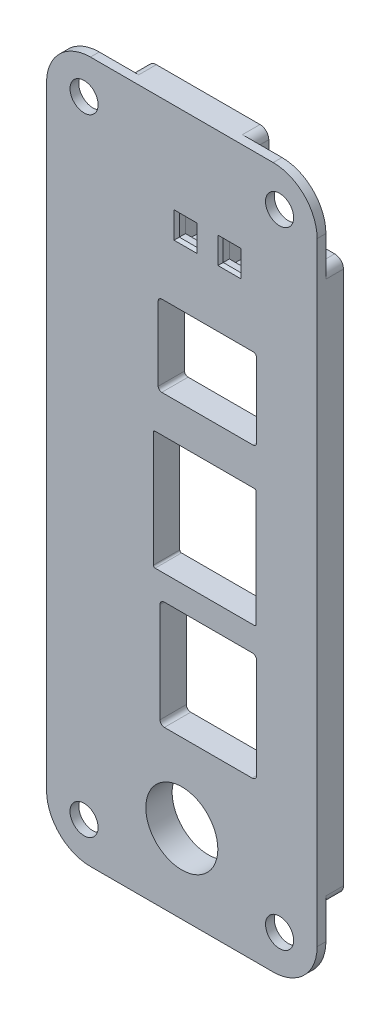
SolidWorks part; units mm, degrees
ref_plane "Front Plane" through (0, 0, 0) normal (0, 0, 1) x (1, 0, 0)
ref_plane "Top Plane" through (0, 0, 0) normal (0, 1, 0) x (1, 0, 0)
ref_plane "Right Plane" through (0, 0, 0) normal (1, 0, 0) x (0, 0, -1)
other "Configuration Table"
sketch "草图1" plane through (0, 0, 0) normal (0, 0, 1) x (1, 0, 0)
  line L0 (47.5, 0) -> (47.4, 0) construction
  line L1 (47.5, -35) -> (47.5, 35) construction
  line L2 (47.4, -34.9) -> (47.4, 34.9)
  line L3 (32, 40) -> (32, 39.9) construction
  line L4 (42.5, 40) -> (21.5, 40) construction
  line L5 (21.6, 39.9) -> (42.4, 39.9)
  line L8 (21.6, -39.9) -> (42.4, -39.9)
  line L9 (21.6, -39.9) -> (42.4, -39.9)
  line L10 (21.6, 39.9) -> (42.4, 39.9)
  line L12 (31.4138, 26.9024) -> (33.4138, 26.9024)
  line L15 (16.5, 0) -> (16.6, 0) construction
  line L16 (40.4138, -15.8026) -> (40.5139, -15.8026) construction
  line L17 (40.5139, -21.4776) -> (40.5139, -10.1276)
  line L18 (16.6, -34.9) -> (16.6, 34.9)
  line L19 (30.0139, -21.9776) -> (40.0139, -21.9776)
  line L20 (37.4138, 28.1024) -> (32.4138, 28.1024) construction
  line L21 (31.4138, 26.9024) -> (31.4138, 29.3024)
  line L22 (30.0139, -9.6276) -> (40.0139, -9.6276)
  line L23 (31.4138, 29.3024) -> (33.4138, 29.3024)
  line L24 (33.4138, 26.9024) -> (33.4138, 29.3024)
  line L25 (29.5139, -21.4776) -> (29.5139, -10.1276)
  line L26 (31.4138, 26.9024) -> (33.4138, 29.3024) construction
  line L27 (31.4138, 29.3024) -> (33.4138, 26.9024) construction
  line L28 (36.4138, 29.3024) -> (38.4138, 29.3024)
  line L29 (36.4138, 29.3024) -> (36.4138, 26.9024)
  line L30 (36.4138, 26.9024) -> (38.4138, 26.9024)
  line L31 (40.3644, -0.0546) -> (40.465, -0.0546) construction
  line L32 (38.4138, 29.3024) -> (38.4138, 26.9024)
  line L33 (36.4138, 29.3024) -> (38.4138, 26.9024) construction
  line L34 (40.465, 6.4954) -> (40.465, -6.6046)
  line L35 (34.6144, 6.5954) -> (34.6144, 6.6954) construction
  line L36 (28.9639, 6.6954) -> (40.265, 6.6954)
  line L37 (36.4138, 26.9024) -> (38.4138, 29.3024) construction
  line L38 (28.8639, -0.0546) -> (28.7639, -0.0546) construction
  line L39 (28.7639, 6.4954) -> (28.7639, -6.6046)
  line L40 (34.6139, -6.7046) -> (34.6139, -6.8046) construction
  line L41 (28.9639, -6.8046) -> (40.265, -6.8046)
  line L50 (40.5138, 11.3024) -> (40.5138, 19.7024)
  line L51 (29.7138, 20.1024) -> (40.1138, 20.1024)
  line L52 (29.3138, 11.3024) -> (29.3138, 19.7024)
  line L53 (29.7138, 10.9024) -> (40.1138, 10.9024)
  arc A0 (42.4, -39.9) -> (47.4, -34.9) centre (42.4, -34.9) ccw
  arc A1 (21.6, -39.9) -> (16.6, -34.9) centre (21.6, -34.9) cw
  arc A2 (47.4, 34.9) -> (42.4, 39.9) centre (42.4, 34.9) ccw
  arc A3 (16.6, 34.9) -> (21.6, 39.9) centre (21.6, 34.9) cw
  arc A4 (30.0139, -21.9776) -> (29.5139, -21.4776) centre (30.0139, -21.4776) cw
  arc A5 (40.0139, -21.9776) -> (40.5139, -21.4776) centre (40.0139, -21.4776) ccw
  arc A6 (40.5139, -10.1276) -> (40.0139, -9.6276) centre (40.0139, -10.1276) ccw
  arc A7 (29.5139, -10.1276) -> (30.0139, -9.6276) centre (30.0139, -10.1276) cw
  arc A8 (28.7639, 6.4954) -> (28.9639, 6.6954) centre (28.9639, 6.4954) cw
  arc A9 (40.465, 6.4954) -> (40.265, 6.6954) centre (40.265, 6.4954) ccw
  arc A10 (28.9639, -6.8046) -> (28.7639, -6.6046) centre (28.9639, -6.6046) cw
  arc A11 (40.265, -6.8046) -> (40.465, -6.6046) centre (40.265, -6.6046) ccw
  arc A12 (29.7138, 10.9024) -> (29.3138, 11.3024) centre (29.7138, 11.3024) cw
  arc A13 (40.1138, 10.9024) -> (40.5138, 11.3024) centre (40.1138, 11.3024) ccw
  arc A14 (40.5138, 19.7024) -> (40.1138, 20.1024) centre (40.1138, 19.7024) ccw
  arc A15 (29.3138, 19.7024) -> (29.7138, 20.1024) centre (29.7138, 19.7024) cw
  point P16 (32, -39.9)
  point P36 (40.5139, -15.8026)
  point P39 (35.0139, -21.9776)
  point P46 (35.0139, -9.6276)
  point P53 (29.5139, -15.8026)
  point P58 (40.4644, -0.0546)
  point P72 (40.465, -0.0546)
  point P78 (34.6144, 6.6954)
  point P84 (28.7639, -0.0546)
  point P89 (34.6139, -6.8046)
  point P112 (40.5138, 15.5024)
  point P117 (34.9138, 20.1024)
  point P118 (29.3138, 15.5024)
  point P123 (34.9138, 10.9024)
  dimension "D1" = 5
  dimension "D2" = 0.5
  dimension "D3" = 0.2
  dimension "D4" = 0.4
  dimension "D5" = 8
extrude "凸台-拉伸1" add sketch "草图1" against normal blind 3
sketch "草图2" plane through (0, 0, -3) normal (0, 0, -1) x (-1, 0, 0)
  line L0 (-16.6, -19) -> (-16.6, 19)
  line L2 (-16.6, -34.9) -> (-16.6, 34.9) construction
  line L3 (-16.6, -19) -> (-27.6, -19)
  line L4 (-27.6, -19) -> (-27.6, 19)
  line L5 (-27.6, 19) -> (-16.6, 19)
  point P5 (-16.6, 0)
extrude "切除-拉伸1" cut sketch "草图2" against normal blind 1
sketch "草图3" plane through (0, 0, -3) normal (0, 0, -1) x (-1, 0, 0)
  line L0 (-47.4, -31.4) -> (-38.9, -31.4)
  line L1 (-47.4, -34.9) -> (-47.4, 34.9) construction
  line L2 (-38.9, -31.4) -> (-38.9, -39.9)
  line L3 (-21.6, -39.9) -> (-42.4, -39.9) construction
  line L5 (-42.4, -39.9) -> (-38.9, -39.9)
  line L6 (-47.4, -34.9) -> (-47.4, -31.4)
  line L7 (-47.4, 0) -> (-16.6, 0) construction
  line L8 (-16.6, -19) -> (-16.6, 19) construction
  line L9 (-32, 0) -> (-32, -4.0641) construction
  line L10 (-47.4, 34.9) -> (-47.4, 31.4)
  line L11 (-42.4, 39.9) -> (-38.9, 39.9)
  line L12 (-38.9, 31.4) -> (-38.9, 39.9)
  line L13 (-47.4, 31.4) -> (-38.9, 31.4)
  line L15 (-16.6, 31.4) -> (-25.1, 31.4)
  line L16 (-25.1, 31.4) -> (-25.1, 39.9)
  line L17 (-21.6, 39.9) -> (-25.1, 39.9)
  line L18 (-16.6, 34.9) -> (-16.6, 31.4)
  line L19 (-16.6, -34.9) -> (-16.6, -31.4)
  line L20 (-21.6, -39.9) -> (-25.1, -39.9)
  line L21 (-25.1, -31.4) -> (-25.1, -39.9)
  line L22 (-16.6, -31.4) -> (-25.1, -31.4)
  arc A0 (-42.4, -39.9) -> (-47.4, -34.9) centre (-42.4, -34.9) cw
  arc A1 (-42.4, 39.9) -> (-47.4, 34.9) centre (-42.4, 34.9) ccw
  arc A2 (-21.6, 39.9) -> (-16.6, 34.9) centre (-21.6, 34.9) cw
  arc A3 (-21.6, -39.9) -> (-16.6, -34.9) centre (-21.6, -34.9) ccw
extrude "切除-拉伸2" cut sketch "草图3" against normal blind 2
sketch "草图4" plane through (0, 0, -1) normal (0, 0, -1) x (-1, 0, 0)
  line L0 (-47.4, 0) -> (-16.6, 0) construction
  line L1 (-47.4, -31.4) -> (-47.4, 31.4) construction
  line L2 (-16.6, -19) -> (-16.6, 19) construction
  line L3 (-32, 0) -> (-32, -3.4003) construction
  circle A0 centre (-20.8723, 35.6277) radius 1.6
  circle A2 centre (-20.8723, -35.6277) radius 1.6
  circle A3 centre (-43.1277, -35.6277) radius 1.6
  circle A4 centre (-43.1277, 35.6277) radius 1.6
extrude "切除-拉伸3" cut sketch "草图4" against normal through all
sketch "草图6" plane through (0, 0, -3) normal (0, 0, -1) x (-1, 0, 0)
  line L0 (-36.4138, 29.3024) -> (-38.4138, 26.9024) construction
  line L1 (-38.5138, 30.1024) -> (-36.3138, 30.1024)
  line L2 (-38.5138, 30.1024) -> (-38.5138, 26.1024)
  line L3 (-38.5138, 26.1024) -> (-36.3138, 26.1024)
  line L4 (-36.3138, 30.1024) -> (-36.3138, 26.1024)
  line L5 (-38.5138, 30.1024) -> (-36.3138, 26.1024) construction
  line L6 (-38.5138, 26.1024) -> (-36.3138, 30.1024) construction
  line L8 (-33.5138, 30.1024) -> (-31.3138, 30.1024)
  line L9 (-33.5138, 30.1024) -> (-33.5138, 26.1024)
  line L10 (-33.5138, 26.1024) -> (-31.3138, 26.1024)
  line L11 (-31.3138, 30.1024) -> (-31.3138, 26.1024)
  line L12 (-33.5138, 30.1024) -> (-31.3138, 26.1024) construction
  line L13 (-33.5138, 26.1024) -> (-31.3138, 30.1024) construction
  point P0 (-37.4138, 28.1024)
  point P9 (-32.4138, 28.1024)
extrude "切除-拉伸4" cut sketch "草图6" against normal blind 2
sketch "草图7" plane through (0, 0, 0) normal (0, 0, 1) x (1, 0, 0)
  line L0 (32, -39.9) -> (32, -21.9776) construction
  line L1 (30.0139, -21.9776) -> (40.0139, -21.9776) construction
  circle A1 centre (32, -30.9388) radius 4.1
extrude "切除-拉伸5" cut sketch "草图7" against normal through all
fillet "圆角1" radius 1 8 edges at (47.4, 31.4, -2) (47.4, -31.4, -2) (38.9, -39.9, -2) (25.1, -39.9, -2) (16.6, -31.4, -2) (38.9, 39.9, -2) (25.1, 39.9, -2) (16.6, 31.4, -2)
chamfer "倒角1" distance 0.3 angle 45 8 edges at (38.4138, 28.1024, 0) (37.4138, 29.3024, 0) (37.4138, 26.9024, 0) (36.4138, 28.1024, 0) (33.4138, 28.1024, 0) (32.4138, 29.3024, 0) (32.4138, 26.9024, 0) (31.4138, 28.1024, 0)
